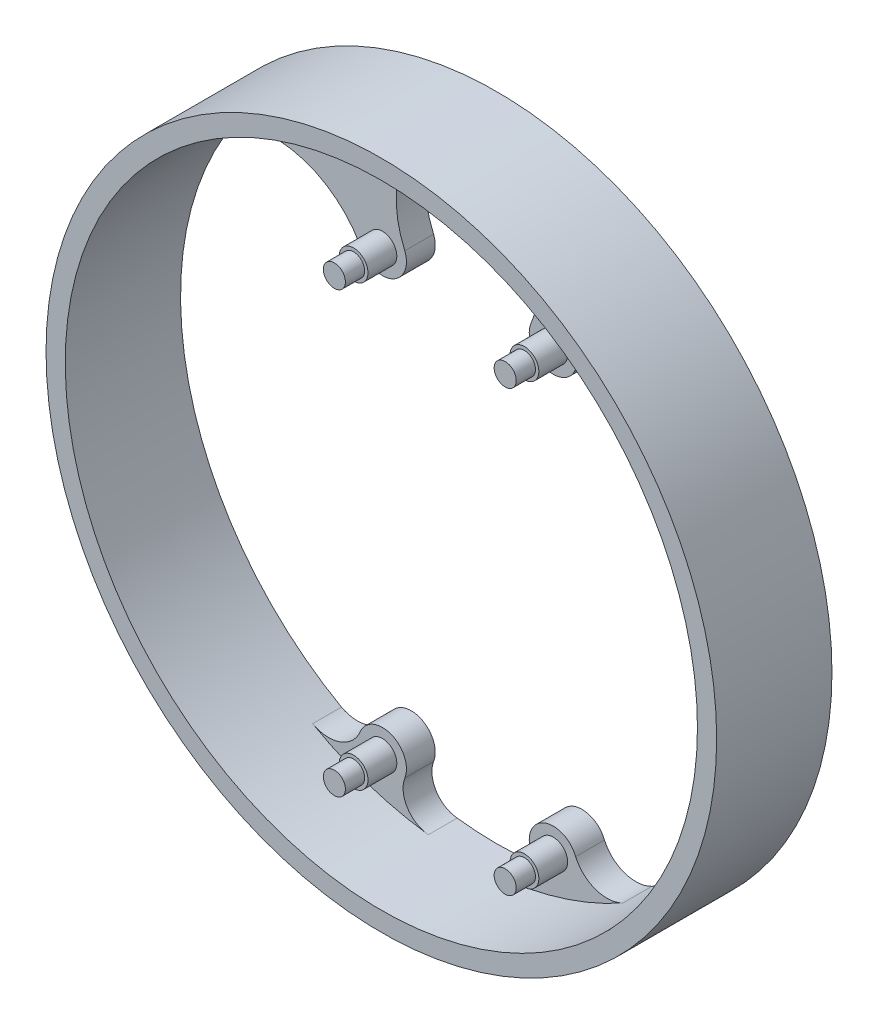
SolidWorks part; units mm, degrees
ref_plane "Plan de face" through (0, 0, 0) normal (0, 0, 1) x (1, 0, 0)
ref_plane "Plan de dessus" through (0, 0, 0) normal (0, 1, 0) x (1, 0, 0)
ref_plane "Plan de droite" through (0, 0, 0) normal (1, 0, 0) x (0, 0, -1)
sketch "Esquisse_carte_mère" plane through (0, 0, 0) normal (0, 0, 1) x (1, 0, 0)
  line L0 (-11.3435, -28.5174) -> (-11.0897, -29.13)
  line L1 (-11.0897, -29.13) -> (-10.6861, -29.6561)
  line L2 (-10.6861, -29.6561) -> (-10.16, -30.0597)
  line L3 (-10.16, -30.0597) -> (-9.5474, -30.3135)
  line L4 (-9.5474, -30.3135) -> (-8.89, -30.4)
  line L5 (-8.89, -30.4) -> (-2.413, -30.4)
  line L6 (-2.413, -30.4) -> (-1.905, -29.892)
  line L7 (-1.905, -29.892) -> (1.905, -29.892)
  line L8 (1.905, -29.892) -> (2.413, -30.4)
  line L9 (2.413, -30.4) -> (8.89, -30.4)
  line L10 (8.89, -30.4) -> (9.5474, -30.3135)
  line L11 (9.5474, -30.3135) -> (10.16, -30.0597)
  line L12 (10.16, -30.0597) -> (10.6861, -29.6561)
  line L13 (10.6861, -29.6561) -> (11.0897, -29.13)
  line L14 (11.0897, -29.13) -> (11.3435, -28.5174)
  line L15 (11.3435, -28.5174) -> (11.43, -27.86)
  line L16 (11.43, -27.86) -> (11.43, 17.86)
  line L17 (11.43, 17.86) -> (11.3435, 18.5174)
  line L18 (11.3435, 18.5174) -> (11.0897, 19.13)
  line L19 (11.0897, 19.13) -> (10.6861, 19.6561)
  line L20 (10.6861, 19.6561) -> (10.16, 20.0597)
  line L21 (10.16, 20.0597) -> (9.5474, 20.3135)
  line L22 (9.5474, 20.3135) -> (8.89, 20.4)
  line L23 (8.89, 20.4) -> (-8.89, 20.4)
  line L24 (-8.89, 20.4) -> (-9.5474, 20.3135)
  line L25 (-9.5474, 20.3135) -> (-10.16, 20.0597)
  line L26 (-10.16, 20.0597) -> (-10.6861, 19.6561)
  line L27 (-10.6861, 19.6561) -> (-11.0897, 19.13)
  line L28 (-11.0897, 19.13) -> (-11.3435, 18.5174)
  line L29 (-11.3435, 18.5174) -> (-11.43, 17.86)
  line L30 (-11.43, 17.86) -> (-11.43, -27.86)
  line L31 (-11.43, -27.86) -> (-11.3435, -28.5174)
  line L32 (8.9522, -28.0199) -> (-18113.3609, 46572.2136) construction
  line L33 (-8.9266, -27.9541) -> (18113.3865, 46572.2795) construction
  circle A0 centre (-3.3, -25.05) radius 0.4
  circle A1 centre (3.3, -25.05) radius 0.4
  circle A2 centre (-3.6, -27.86) radius 0.45
  circle A3 centre (3.6, -27.86) radius 0.45
  circle A4 centre (10.16, 14.05) radius 0.5
  circle A5 centre (10.16, 11.51) radius 0.5
  circle A6 centre (10.16, 8.97) radius 0.5
  circle A7 centre (10.16, 6.43) radius 0.5
  circle A8 centre (10.16, 3.89) radius 0.5
  circle A9 centre (10.16, 1.35) radius 0.5
  circle A10 centre (10.16, -1.19) radius 0.5
  circle A11 centre (10.16, -3.73) radius 0.5
  circle A12 centre (10.16, -6.27) radius 0.5
  circle A13 centre (10.16, -8.81) radius 0.5
  circle A14 centre (10.16, -11.35) radius 0.5
  circle A15 centre (10.16, -13.89) radius 0.5
  circle A16 centre (-10.16, -24.05) radius 0.5
  circle A17 centre (-10.16, -21.51) radius 0.5
  circle A18 centre (-10.16, -18.97) radius 0.5
  circle A19 centre (-10.16, -16.43) radius 0.5
  circle A20 centre (-10.16, -13.89) radius 0.5
  circle A21 centre (-10.16, -11.35) radius 0.5
  circle A22 centre (-10.16, -8.81) radius 0.5
  circle A23 centre (-10.16, -6.27) radius 0.5
  circle A24 centre (-10.16, -3.73) radius 0.5
  circle A25 centre (-10.16, -1.19) radius 0.5
  circle A26 centre (-10.16, 1.35) radius 0.5
  circle A27 centre (-10.16, 3.89) radius 0.5
  circle A28 centre (-10.16, 6.43) radius 0.5
  circle A29 centre (-10.16, 8.97) radius 0.5
  circle A30 centre (-10.16, 11.51) radius 0.5
  circle A31 centre (-10.16, 14.05) radius 0.5
  circle A32 centre (-8.89, -27.86) radius 1.25
  circle A33 centre (8.89, -27.86) radius 1.25
  circle A34 centre (-8.89, 17.86) radius 1.25
  circle A35 centre (8.89, 17.86) radius 1.25
  circle A36 centre (-1.95, -25.955) radius 0.35
  circle A37 centre (1.95, -25.955) radius 0.35
  circle A38 centre (-2.2, 15.706) radius 0.45
  circle A39 centre (3.048, -15.795) radius 0.25
  circle A40 centre (1.016, -20.875) radius 0.25
  circle A41 centre (-6.223, -9.826) radius 0.25
  circle A42 centre (-6.096, -16.43) radius 0.25
  circle A43 centre (7.3914, -2.0028) radius 0.25
  circle A44 centre (7.366, -18.462) radius 0.25
  circle A45 centre (-1.905, 12.018) radius 0.25
  circle A46 centre (1.905, 9.224) radius 0.25
  circle A47 centre (-5.715, -21.129) radius 0.25
  circle A48 centre (-4.064, -1.571) radius 0.25
  circle A49 centre (-8.509, -22.78) radius 0.25
  circle A50 centre (0.2286, -14.5758) radius 0.25
  circle A51 centre (0.508, 7.446) radius 0.25
  circle A52 centre (0.635, 8.589) radius 0.25
  circle A53 centre (-7.112, 0.334) radius 0.25
  circle A54 centre (4.953, -15.795) radius 0.25
  circle A55 centre (0, 10.494) radius 0.25
  circle A56 centre (-4.191, -16.43) radius 0.25
  circle A57 centre (-0.889, -17.573) radius 0.25
  circle A58 centre (5.842, -10.715) radius 0.25
  circle A59 centre (2.159, -17.446) radius 0.25
  circle A60 centre (0, -27.987) radius 0.25
  circle A61 centre (-1.397, 4.271) radius 0.25
  circle A62 centre (-5.207, 1.985) radius 0.25
  circle A63 centre (-0.381, -6.651) radius 0.25
  circle A64 centre (6.858, 8.462) radius 0.25
  circle A65 centre (5.207, 3.128) radius 0.25
  circle A66 centre (2.667, 4.525) radius 0.25
  circle A67 centre (5.08, 11.764) radius 0.25
  circle A68 centre (0, 14.431) radius 0.25
  circle A69 centre (-1.778, 8.716) radius 0.25
  circle A70 centre (-2.921, 4.271) radius 0.25
  circle A71 centre (-5.588, 3.128) radius 0.25
  circle A72 centre (-1.905, -19.732) radius 0.25
  circle A73 centre (-5.842, -8.683) radius 0.25
  circle A74 centre (-3.048, -20.113) radius 0.25
  circle A75 centre (-6.604, -7.667) radius 0.25
  circle A76 centre (-5.207, -10.842) radius 0.25
  circle A77 centre (10.668, -26.082) radius 0.25
  circle A78 centre (5.969, -4.365) radius 0.25
  circle A79 centre (5.08, -9.191) radius 0.25
  circle A80 centre (-3.81, -3.349) radius 0.25
  circle A81 centre (-4.953, -9.699) radius 0.25
  circle A82 centre (3.048, 6.43) radius 0.25
  circle A83 centre (5.969, -3.222) radius 0.25
  circle A84 centre (6.858, -7.667) radius 0.25
  circle A85 centre (6.477, 6.303) radius 0.25
  circle A86 centre (-1.27, 10.367) radius 0.25
  circle A87 centre (-1.0922, -0.1994) radius 0.25
  circle A88 centre (0.508, -0.428) radius 0.25
  circle A89 centre (4.318, -17.065) radius 0.25
  circle A90 centre (1.524, 4.144) radius 0.25
  circle A91 centre (-2.921, -1.444) radius 0.25
  circle A92 centre (3.302, -10.08) radius 0.25
  circle A93 centre (-3.81, -10.08) radius 0.25
  circle A94 centre (-5.08, -6.778) radius 0.25
  point P222 (0, -5)
  dimension "D5" = 2.5
  dimension "D1" = 2.54
  dimension "D2" = 2.54
  dimension "D3" = 2.54
  dimension "D4" = 2.54
sketch "Esquisse_corps" plane through (0, 0, 0) normal (0, 0, 1) x (1, 0, 0)
  line L0 (0, 0) -> (0, -50000) construction
  line L1 (0, 0) -> (-50000, 0) construction
  line L2 (-8.89, -27.86) -> (46591.3436, -18150.1731) construction
  line L3 (-72498.1788, -186428.8884) -> (90602.6387, 232973.2138) construction
  line L4 (-8.89, 17.86) -> (46591.3436, 18140.1731) construction
  line L5 (72498.2044, -186428.9542) -> (-90602.6131, 232973.148) construction
  circle A1 centre (0, 0) radius 34.9
  arc A2 (-11.22, -26.9539) -> (-6.56, -28.7661) centre (-8.89, -27.86) cw
  arc A3 (-11.22, -26.9539) -> (-16.1545, -28.6608) centre (-14.4856, -25.4993) cw
  arc A4 (-6.56, -28.7661) -> (-4.1089, -32.6424) centre (-3.8447, -29.7623) ccw
  circle A5 centre (0, 0) radius 32.9 construction
  arc A7 (6.56, -28.7661) -> (4.1089, -32.6424) centre (3.8447, -29.7623) cw
  arc A8 (11.22, -26.9539) -> (16.1545, -28.6608) centre (14.4856, -25.4993) ccw
  arc A9 (11.22, -26.9539) -> (6.56, -28.7661) centre (8.89, -27.86) ccw
  arc A10 (-11.22, 16.9539) -> (-6.56, 18.7661) centre (-8.89, 17.86) ccw
  arc A11 (-6.56, 18.7661) -> (0, 32.9) centre (2.9026, 22.9635) cw
  arc A12 (-25.6489, 20.6044) -> (-11.22, 16.9539) centre (-20.1793, 11.8825) cw
  arc A15 (25.6489, 20.6044) -> (11.22, 16.9539) centre (20.1793, 11.8825) ccw
  arc A16 (6.56, 18.7661) -> (0, 32.9) centre (-2.9026, 22.9635) ccw
  arc A17 (11.22, 16.9539) -> (6.56, 18.7661) centre (8.89, 17.86) cw
  arc A18 (-25.6489, 20.6044) -> (-16.1545, -28.6608) centre (0, 0) ccw
  arc A19 (-4.1089, -32.6424) -> (4.1089, -32.6424) centre (0, 0) ccw
  arc A20 (16.1545, -28.6608) -> (25.6489, 20.6044) centre (0, 0) ccw
  point P9 (0, 0)
  dimension "D2" = 69.8
  dimension "D4" = 2.5
  dimension "D6" = 2.5
  dimension "D3" = 90
  dimension "D5" = 90
extrude "Boss.-Extru.1" add sketch "Esquisse_corps" along normal blind 3
sketch "Esquisse5" plane through (0, 0, 3) normal (0, 0, 1) x (1, 0, 0)
  line L0 (0, 0) -> (0, -50000) construction
  line L1 (0, 0) -> (50000, 0) construction
  circle A0 centre (-8.89, 17.86) radius 1.5
  circle A1 centre (-8.89, -27.86) radius 1.5
  circle A2 centre (8.89, -27.86) radius 1.5
  circle A3 centre (8.89, 17.86) radius 1.5
  dimension "D1" = 3
  dimension "D2" = 3
extrude "Boss.-Extru.2" add sketch "Esquisse5" along normal blind 3
sketch "Esquisse6" plane through (0, 0, 6) normal (0, 0, 1) x (1, 0, 0)
  line L0 (0, -5) -> (0, 21.3578) construction
  circle A0 centre (-8.89, 17.86) radius 1.15
  circle A1 centre (-8.89, -27.86) radius 1.15
  circle A2 centre (8.89, -27.86) radius 1.15
  circle A3 centre (8.89, 17.86) radius 1.15
  dimension "D1" = 2.3
  dimension "D2" = 2.3
extrude "Boss.-Extru.3" add sketch "Esquisse6" along normal blind 2
sketch "Esquisse7" plane through (0, 0, 3) normal (0, 0, 1) x (1, 0, 0)
  circle A0 centre (0, 0) radius 34.9
  circle A1 centre (0, 0) radius 32.9
extrude "Boss.-Extru.4" add sketch "Esquisse7" along normal blind 9
